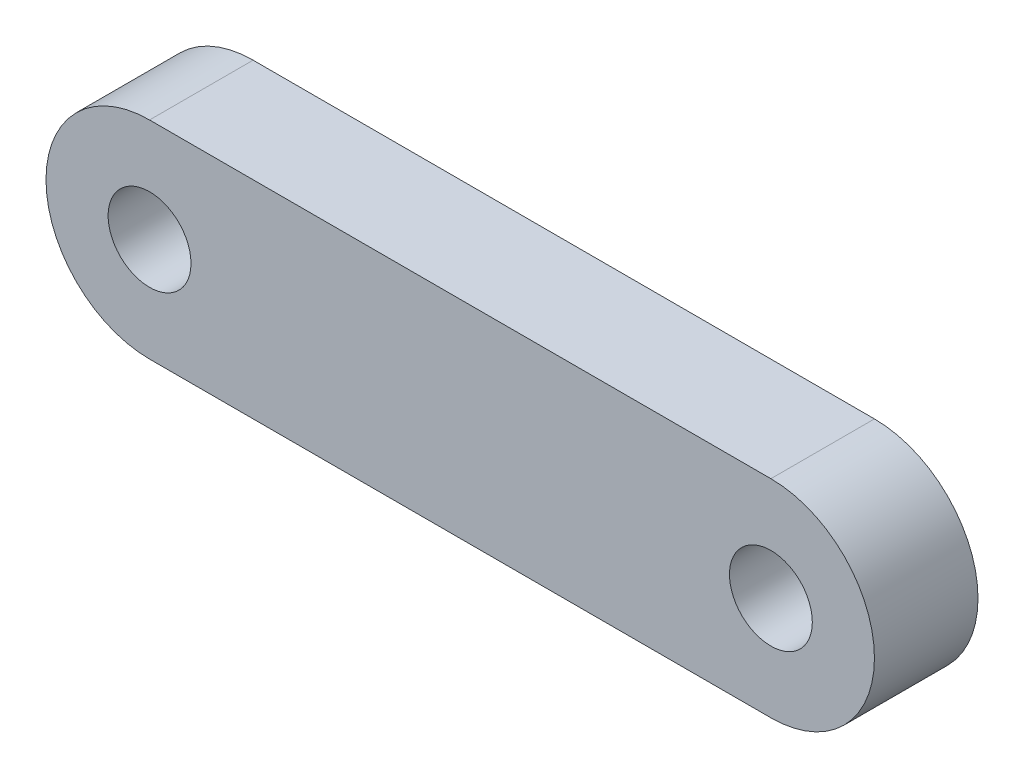
SolidWorks part; units mm, degrees
material "AISI 316 Stainless Steel Sheet (SS)"
ref_plane "Front Plane" through (0, 0, 0) normal (0, 0, 1) x (1, 0, 0)
ref_plane "Top Plane" through (0, 0, 0) normal (0, 1, 0) x (1, 0, 0)
ref_plane "Right Plane" through (0, 0, 0) normal (1, 0, 0) x (0, 0, -1)
sketch "Sketch1" plane through (0, 0, 0) normal (0, 0, 1) x (1, 0, 0)
  line L0 (-30, 0) -> (30, 0) construction
  line L1 (-30, 10) -> (30, 10)
  line L2 (-30, -10) -> (30, -10)
  arc A0 (-30, 10) -> (-30, -10) centre (-30, 0) ccw
  arc A1 (30, -10) -> (30, 10) centre (30, 0) ccw
  point P2 (0, 0)
  dimension "D1" = 20
  dimension "D2" = 60
extrude "Boss-Extrude1" add sketch "Sketch1" along normal mid plane 10
hole_wizard "Ø8.0mm Dowel Hole1" positions "Sketch2" profile "Sketch3" hole size "Ø8.0" standard "ISO" end condition through all
sketch "Sketch2" plane through (0, 0, 5) normal (0, 0, 1) x (1, 0, 0)
  point P0 (-30, 0)
  point P3 (30, 0)
sketch "Sketch3" plane through (-30, 0, 5) normal (1, 0, 0) x (0, -1, 0)
  line L0 (0, 0) -> (0, 10)
  line L1 (0, 10) -> (4, 10)
  line L2 (4, 10) -> (4, 0)
  line L5 (4, 0) -> (0, 0)
  line L11 (0, -6.35) -> (0, 107.95) construction
  dimension "Thru Hole Dia." = 8
  dimension "Thru Hole Depth" = 10
ref_point "Point1"
ref_point "Point2"
sketch "Sketch4" plane through (0, 0, 5) normal (0, 0, 1) x (1, 0, 0)
  point P0 (30, 0)
